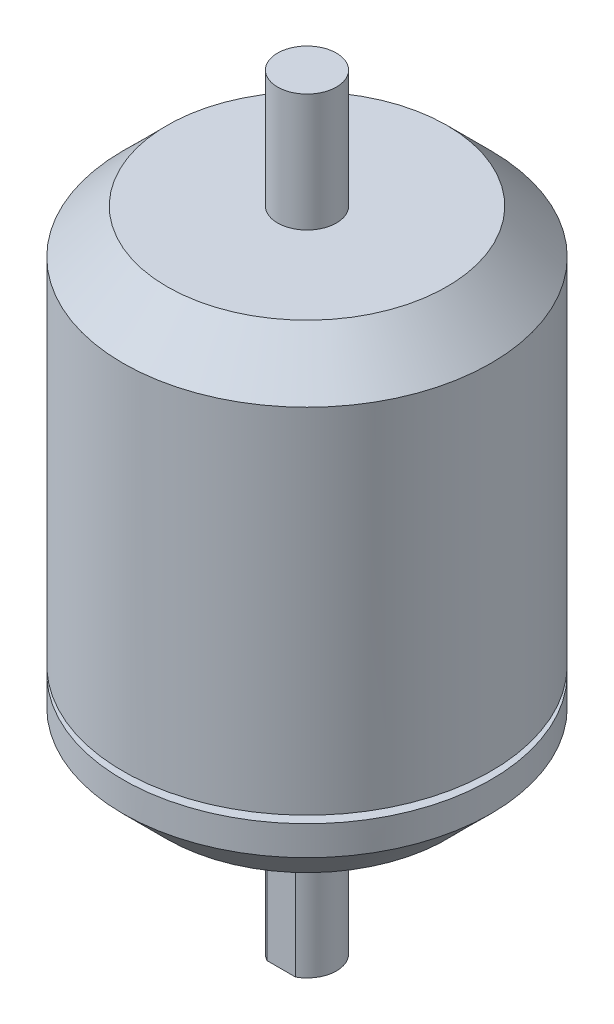
SolidWorks part; units mm, degrees
ref_plane "Front Plane" through (0, 0, 0) normal (0, 0, 1) x (1, 0, 0)
ref_plane "Top Plane" through (0, 0, 0) normal (0, 1, 0) x (1, 0, 0)
ref_plane "Right Plane" through (0, 0, 0) normal (1, 0, 0) x (0, 0, -1)
sketch "Sketch1" plane through (0, 0, 0) normal (0, 1, 0) x (1, 0, 0)
  circle A0 centre (0, 0) radius 25
  dimension "D1" = 50
extrude "Boss-Extrude1" add sketch "Sketch1" along normal blind 65
chamfer "Chamfer1" distance 6 angle 45 2 edges at (0, 0, 25) (0, 65, 25)
sketch "Sketch2" plane through (0, 65, 0) normal (0, 1, 0) x (1, 0, 0)
  circle A0 centre (0, 0) radius 4
  dimension "D1" = 8
extrude "Boss-Extrude2" add sketch "Sketch2" along normal blind 16
sketch "Sketch4" plane through (0, 0, 0) normal (0, -1, 0) x (1, 0, 0)
  circle A0 centre (0, 0) radius 4
  dimension "D1" = 8
extrude "Boss-Extrude3" add sketch "Sketch4" along normal blind 23
sketch "Sketch5" plane through (0, -23, 0) normal (0, -1, 0) x (1, 0, 0)
  line L1 (-1.9365, 3.5) -> (1.9365, 3.5)
  circle A1 centre (0, 0) radius 4 construction
  circle A2 centre (0, 0) radius 4 construction
  arc A3 (-1.9365, 3.5) -> (1.9365, 3.5) centre (0, 0) cw
  dimension "D1" = 3.5
extrude "Cut-Extrude4" cut sketch "Sketch5" against normal blind 20
sketch "Sketch6" plane through (0, 0, 0) normal (0, -1, 0) x (-1, 0, 0)
  circle A0 centre (0, 0) radius 15 construction
  circle A1 centre (15, 0) radius 2
  circle A2 centre (0, -15) radius 2
  circle A3 centre (-15, 0) radius 2
  circle A4 centre (0, 15) radius 2
  point P14 (0, 0)
  dimension "D1" = 30
  dimension "D2" = 4
  dimension "D3" = 4
extrude "Cut-Extrude5" cut sketch "Sketch6" against normal blind 20
sketch "Sketch7" plane through (0, 0, 0) normal (0, -1, 0) x (1, 0, 0)
  circle A0 centre (0, 0) radius 25
  circle A1 centre (0, 0) radius 10
  dimension "D1" = 20
extrude "Cut-Extrude6" cut sketch "Sketch7" against normal blind 1 from offset 10
